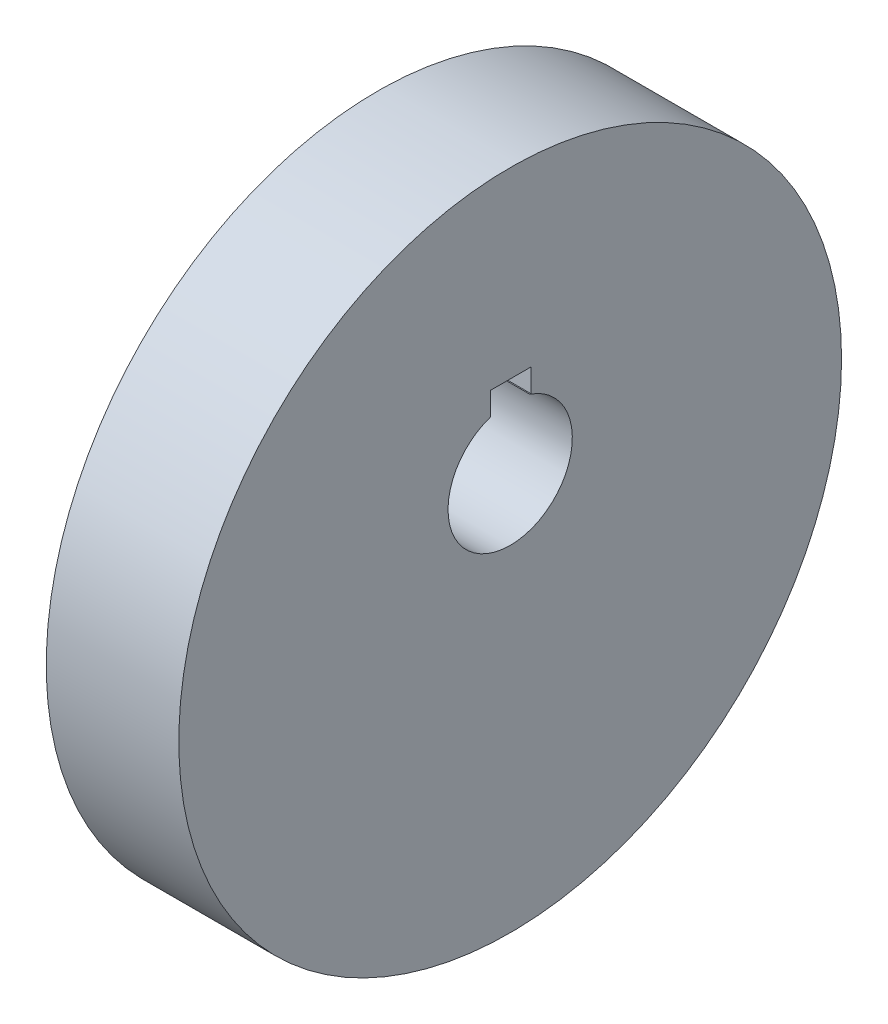
SolidWorks part; units mm, degrees
ref_plane "Front Plane" through (0, 0, 0) normal (1, 0, 0) x (0, 1, 0)
ref_plane "Top Plane" through (0, 0, 0) normal (0, 0, 1) x (0, 1, 0)
ref_plane "Right Plane" through (0, 0, 0) normal (0, 1, 0) x (-1, 0, 0)
sketch "Sketch1" plane through (0, 0, 0) normal (1, 0, 0) x (0, 1, 0)
  circle A0 centre (0, 0) radius 25.4
extrude "Boss-Extrude1" add sketch "Sketch1" along normal blind 10.16
sketch "Sketch2" plane through (0, 0, 0) normal (1, 0, 0) x (0, 1, 0)
  circle A0 centre (5.08, 0) radius 4.7625
extrude "Cut-Extrude1" cut sketch "Sketch2" along normal through all
sketch "Sketch3" plane through (0, 0, 0) normal (1, 0, 0) x (0, 1, 0)
  line L1 (9.5981, 1.506) -> (11.3665, 1.506)
  line L2 (9.5981, 1.506) -> (9.5981, -1.5875)
  line L3 (9.5981, -1.5875) -> (11.3665, -1.5875)
  line L4 (11.3665, 1.506) -> (11.3665, -1.5875)
  circle A0 centre (5.08, 0) radius 4.7625 construction
extrude "Cut-Extrude2" cut sketch "Sketch3" along normal through all
